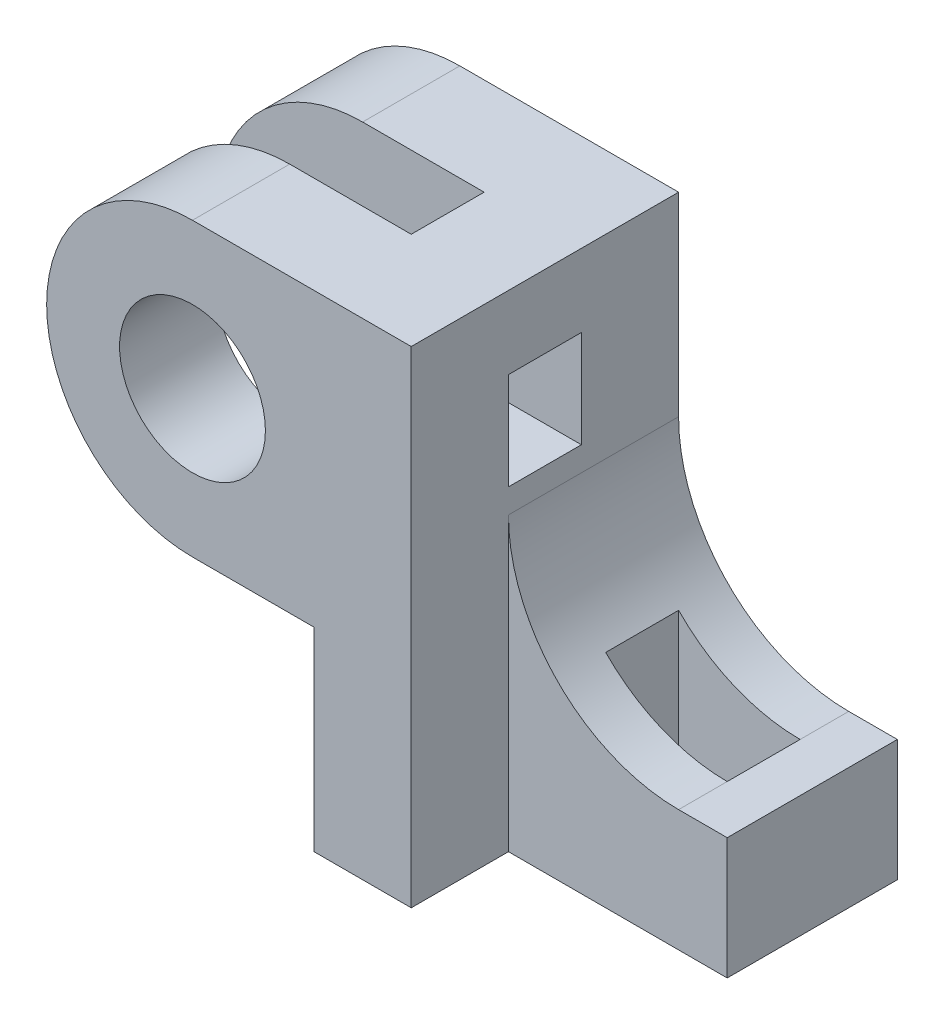
SolidWorks part; units mm, degrees
ref_plane "Front Plane" through (0, 0, 0) normal (0, 0, 1) x (1, 0, 0)
ref_plane "Top Plane" through (0, 0, 0) normal (0, 1, 0) x (1, 0, 0)
ref_plane "Right Plane" through (0, 0, 0) normal (1, 0, 0) x (0, 0, -1)
sketch "Sketch1" plane through (0, 0, 0) normal (0, 0, 1) x (1, 0, 0)
  line L0 (0, 0) -> (0, 100)
  line L1 (0, 100) -> (-45, 100)
  line L2 (-45, 40) -> (-20, 40)
  line L3 (-20, 40) -> (-20, 0)
  line L4 (-20, 0) -> (0, 0)
  arc A0 (-45, 100) -> (-45, 40) centre (-45, 70) ccw
  circle A1 centre (-45, 70) radius 15
  point P9 (0, 0)
  dimension "D4" = 30
  dimension "D6" = 30
  dimension "D1" = 20
  dimension "D2" = 100
  dimension "D3" = 45
  dimension "D5" = 25
extrude "Boss-Extrude1" add sketch "Sketch1" along normal mid plane 55
sketch "Sketch2" plane through (0, 100, 0) normal (0, 1, 0) x (1, 0, 0)
  line L0 (-75, 27.5) -> (-75, -27.5) construction
  line L1 (-75, 7.5) -> (-20, 7.5)
  line L2 (-75, 7.5) -> (-75, -7.5)
  line L3 (-75, -7.5) -> (-20, -7.5)
  line L4 (-20, 7.5) -> (-20, -7.5)
  line L5 (-75, 7.5) -> (-20, -7.5) construction
  line L6 (-75, -7.5) -> (-20, 7.5) construction
  line L7 (0, -27.5) -> (0, 27.5) construction
  point P0 (-47.5, 0)
  point P5 (0, 0)
  dimension "D1" = 15
  dimension "D2" = 20
extrude "Cut-Extrude1" cut sketch "Sketch2" against normal up to next
sketch "Sketch4" plane through (0, 0, -27.5) normal (0, 0, -1) x (-1, 0, 0)
  line L0 (-45, 0) -> (0, 0)
  line L1 (0, 0) -> (0, 60)
  line L3 (-45, 25) -> (-45, 0)
  line L4 (0, 0) -> (0, 100) construction
  line L5 (-45, 25) -> (-35, 25)
  arc A1 (-35, 25) -> (0, 60) centre (-35, 60) ccw
  dimension "D2" = 10
  dimension "D4" = 35
  dimension "D1" = 45
  dimension "D3" = 60
extrude "Boss-Extrude2" add sketch "Sketch4" against normal blind 35
sketch "Sketch5" plane through (0, 0, 0) normal (1, 0, 0) x (0, 0, -1)
  line L0 (-27.5, 100) -> (27.5, 100) construction
  line L1 (-7.5, 65) -> (7.5, 65)
  line L2 (-7.5, 65) -> (-7.5, 85)
  line L3 (-7.5, 85) -> (7.5, 85)
  line L4 (7.5, 65) -> (7.5, 85)
  line L5 (-7.5, 65) -> (7.5, 85) construction
  line L6 (-7.5, 85) -> (7.5, 65) construction
  line L7 (27.5, 60) -> (27.5, 100) construction
  point P0 (0, 75)
  dimension "D1" = 15
  dimension "D2" = 20
  dimension "D3" = 15
  dimension "D4" = 20
extrude "Cut-Extrude2" cut sketch "Sketch5" against normal up to next
sketch "Sketch6" plane through (0, 0, 0) normal (0, -1, 0) x (1, 0, 0)
  line L0 (45, 7.5) -> (45, -27.5) construction
  line L1 (10, -17.5) -> (35, -17.5)
  line L2 (10, -17.5) -> (10, -2.5)
  line L3 (10, -2.5) -> (35, -2.5)
  line L4 (35, -17.5) -> (35, -2.5)
  line L5 (10, -17.5) -> (35, -2.5) construction
  line L6 (10, -2.5) -> (35, -17.5) construction
  line L7 (-20, -27.5) -> (45, -27.5) construction
  point P0 (22.5, -10)
  dimension "D1" = 10
  dimension "D2" = 25
  dimension "D3" = 15
  dimension "D4" = 10
extrude "Cut-Extrude3" cut sketch "Sketch6" against normal up to next
